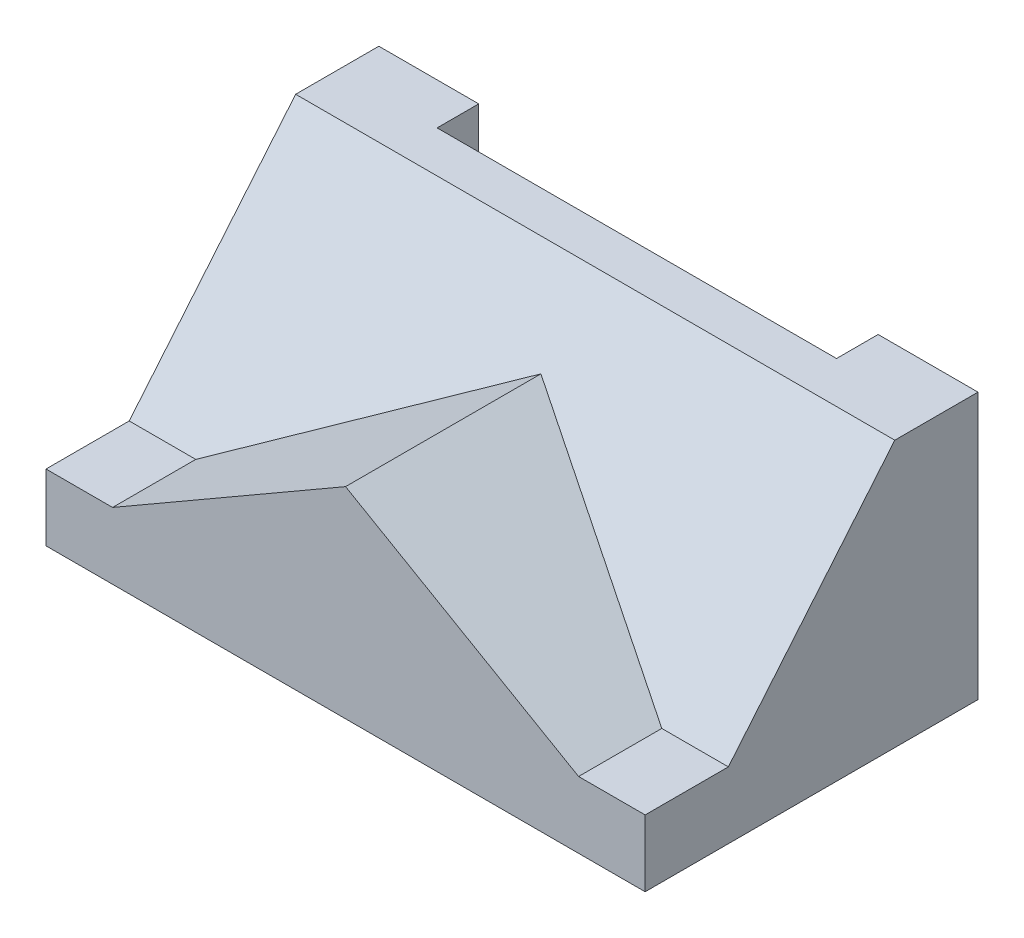
SolidWorks part; units mm, degrees
ref_plane "前基準面" through (0, 0, 0) normal (0, 0, 1) x (1, 0, 0)
ref_plane "上基準面" through (0, 0, 0) normal (0, 1, 0) x (1, 0, 0)
ref_plane "右基準面" through (0, 0, 0) normal (1, 0, 0) x (0, 0, -1)
sketch "草圖1" plane through (0, 0, 0) normal (1, 0, 0) x (0, 0, -1)
  line L0 (0, 0) -> (40, 0)
  line L1 (40, 0) -> (40, 32)
  line L2 (40, 32) -> (30, 32)
  line L3 (30, 32) -> (10, 8)
  line L4 (10, 8) -> (0, 8)
  line L5 (0, 8) -> (0, 0)
  dimension "D1" = 8
  dimension "D2" = 10
  dimension "D3" = 10
  dimension "D4" = 32
  dimension "D5" = 40
extrude "填料-伸長1" add sketch "草圖1" along normal mid plane 72
sketch "草圖2" plane through (0, 0, 0) normal (0, 0, 1) x (1, 0, 0)
  line L0 (0, 0) -> (0, 34.0898) construction
  line L1 (0, 24.1658) -> (-28, 8)
  line L2 (0, 24.1658) -> (28, 8)
  line L4 (-36, 8) -> (-36, 0)
  line L5 (-36, 0) -> (36, 0)
  line L6 (36, 0) -> (36, 8)
  line L7 (36, 8) -> (-36, 8)
  line L8 (-36, 8) -> (-36, 0)
  line L9 (-36, 0) -> (36, 0)
  line L10 (36, 0) -> (36, 8)
  line L11 (28, 8) -> (-28, 8)
  dimension "D2" = 120
  dimension "D3" = 8
  dimension "D1" = 0
extrude "填料-伸長2" add sketch "草圖2" against normal up to next contours L1 L11 L2
sketch "草圖3" plane through (0, 32, 0) normal (0, 1, 0) x (1, 0, 0)
  line L0 (36, 40) -> (-36, 40) construction
  line L1 (-24, 35) -> (24, 35)
  line L2 (-24, 35) -> (-24, 40)
  line L3 (-24, 40) -> (24, 40)
  line L4 (24, 35) -> (24, 40)
  line L5 (0, 0) -> (0, 35) construction
  dimension "D1" = 5
  dimension "D2" = 48
extrude "除料-伸長1" cut sketch "草圖3" against normal through all
